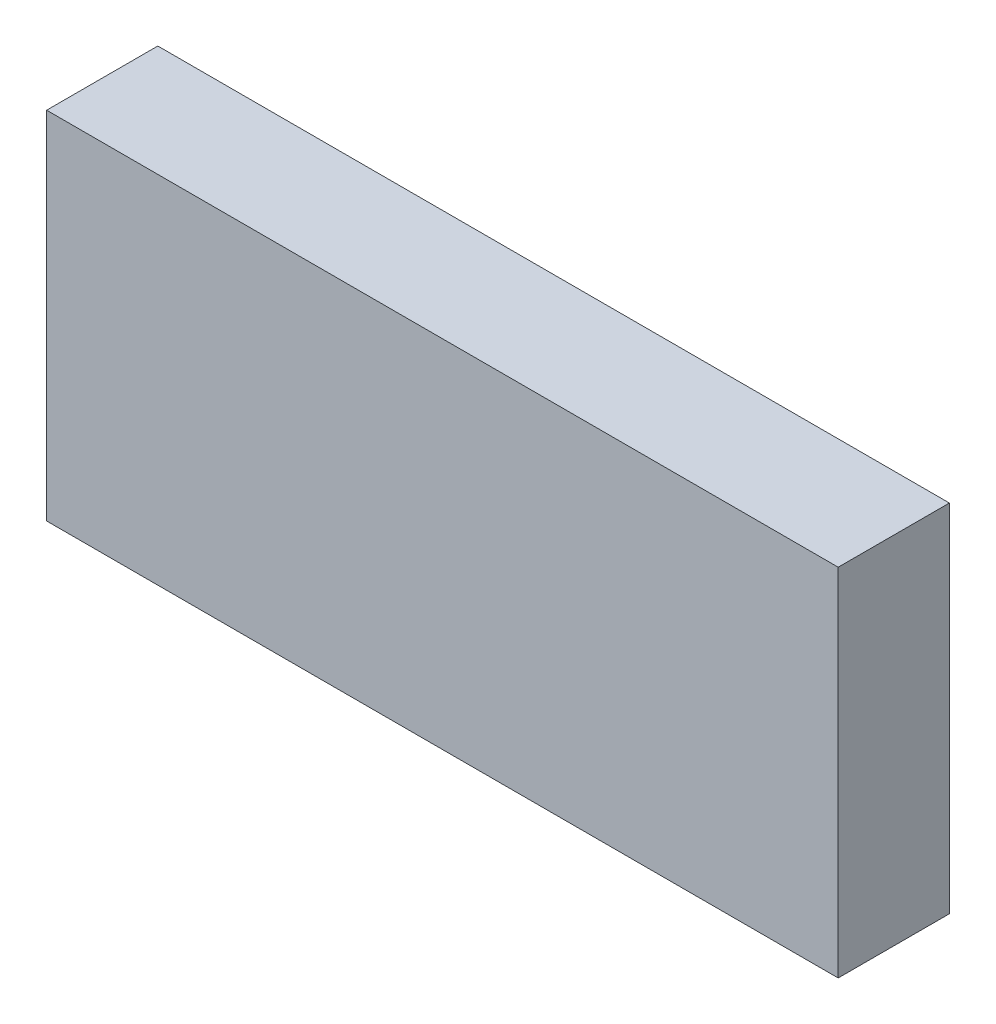
SolidWorks part; units mm, degrees
material "Acrylic (Medium-high impact)"
ref_plane "Front Plane" through (0, 0, 0) normal (0, 0, 1) x (1, 0, 0)
ref_plane "Top Plane" through (0, 0, 0) normal (0, 1, 0) x (1, 0, 0)
ref_plane "Right Plane" through (0, 0, 0) normal (1, 0, 0) x (0, 0, -1)
sketch "Sketch1" plane through (0, 0, 0) normal (0, 0, 1) x (1, 0, 0)
  line L1 (-7.0485, -111.9505) -> (-18.3515, -111.9505)
  line L2 (-7.0485, -111.9505) -> (-7.0485, -106.8705)
  line L3 (-7.0485, -106.8705) -> (-18.3515, -106.8705)
  line L4 (-18.3515, -111.9505) -> (-18.3515, -106.8705)
  dimension "D1" = 5.08
extrude "Boss-Extrude1" add sketch "Sketch1" along normal blind 1.5875
